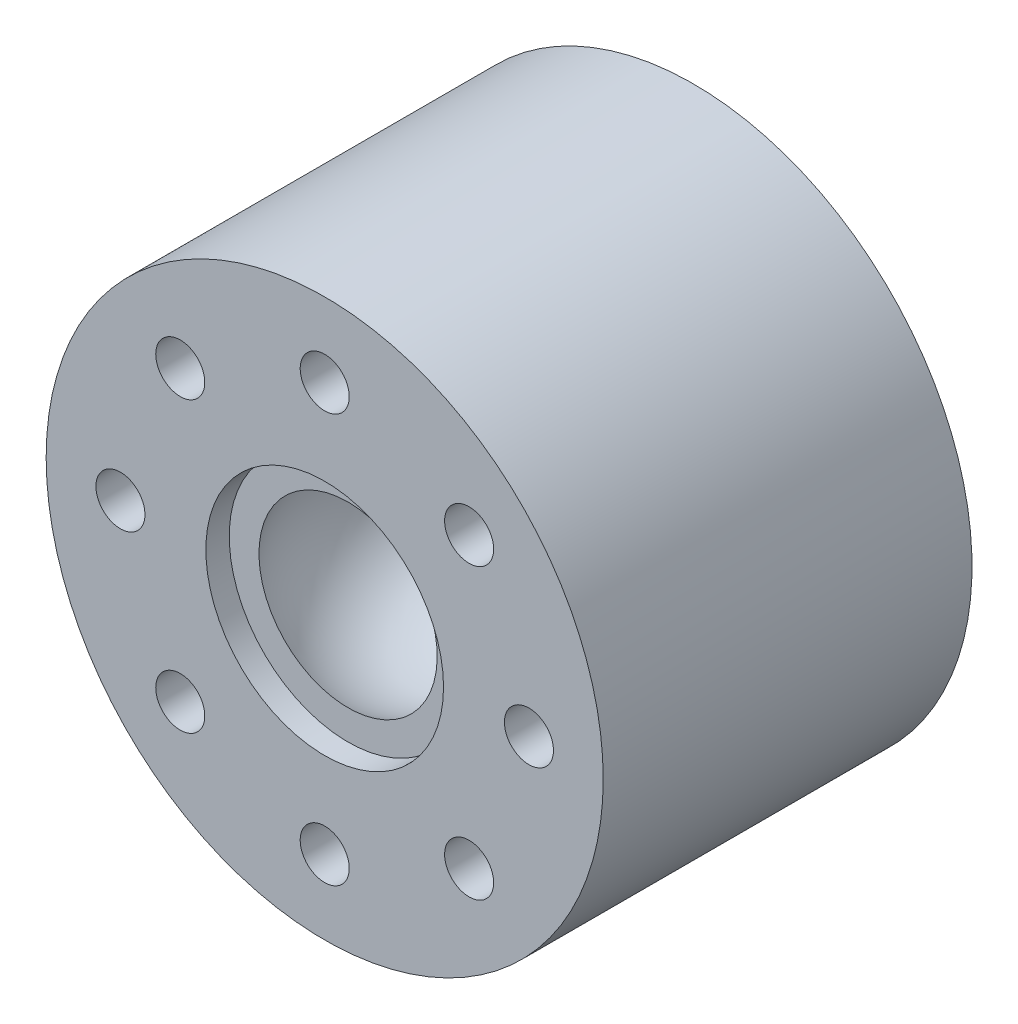
SolidWorks part; units mm, degrees
ref_plane "Front Plane" through (0, 0, 0) normal (0, 0, 1) x (1, 0, 0)
ref_plane "Top Plane" through (0, 0, 0) normal (0, 1, 0) x (1, 0, 0)
ref_plane "Right Plane" through (0, 0, 0) normal (1, 0, 0) x (0, 0, -1)
sketch "Sketch1" plane through (0, 0, 0) normal (0, 0, 1) x (1, 0, 0)
  circle A0 centre (0, 0) radius 37.5
  dimension "D1" = 75
extrude "Boss-Extrude1" add sketch "Sketch1" along normal blind 55
sketch "Sketch2" plane through (0, 0, 55) normal (0, 0, 1) x (1, 0, 0)
  circle A0 centre (0, 0) radius 16
  dimension "D1" = 32
extrude "Cut-Extrude1" cut sketch "Sketch2" against normal blind 16
sketch "Sketch3" plane through (0, 0, 39) normal (0, 0, 1) x (1, 0, 0)
  circle A0 centre (0, 0) radius 16
  dimension "D1" = 32
extrude "Cut-Extrude2" cut sketch "Sketch3" against normal blind 2.5
sketch "Sketch4" plane through (0, 0, 0) normal (1, 0, 0) x (0, 0, -1)
  line L0 (-12.7, 8.9281) -> (-12.7, 0)
  line L1 (-12.7, 0) -> (-36.5, 0)
  line L2 (-36.5, 0) -> (-36.5, 12)
  line L3 (0, -37.5) -> (0, 37.5) construction
  line L4 (-36.5, 16) -> (-36.5, -16) construction
  spline S0 degree 3 poles (-36.5, 12) (-28.3437, 16.5234) (-19.1659, 14.2615) (-12.7, 8.9281) knots 0 0 0 0 1 1 1 1
  dimension "D1" = 8.9281
  dimension "D2" = 12
  dimension "D3" = 12.7
revolve "Cut-Revolve1" cut sketch "Sketch4" angle 360 about L1
sketch "Sketch6" plane through (0, 0, 0) normal (0, 0, -1) x (-1, 0, 0)
  circle A0 centre (0, 0) radius 8.9297
  dimension "D1" = 17.8594
extrude "Cut-Extrude3" cut sketch "Sketch6" against normal blind 12.7
sketch "Sketch7" plane through (0, 0, 55) normal (0, 0, 1) x (1, 0, 0)
  circle A1 centre (0, 0) radius 37.5
  dimension "D1" = 75
extrude "Cut-Extrude4" cut sketch "Sketch7" against normal blind 15.35
sketch "Sketch9" plane through (0, 0, 0) normal (0, 0, -1) x (-1, 0, 0)
  circle A0 centre (0, 0) radius 27.5
  circle A1 centre (0, -27.5) radius 3.302
  circle A2 centre (-19.4454, -19.4454) radius 3.302
  circle A3 centre (-27.5, 0) radius 3.302
  circle A4 centre (-19.4454, 19.4454) radius 3.302
  circle A5 centre (0, 27.5) radius 3.302
  circle A6 centre (19.4454, 19.4454) radius 3.302
  circle A7 centre (27.5, 0) radius 3.302
  circle A8 centre (19.4454, -19.4454) radius 3.302
  point P21 (0, 0)
  dimension "D1" = 55
  dimension "D2" = 6.604
  dimension "D3" = 8
extrude "Cut-Extrude6" cut sketch "Sketch9" against normal through all contours A0 A7 | A0 A7 | A0 A8 | A0 A8 | A0 A1 | A0 A1 | A0 A2 | A0 A2 | A0 A3 | A0 A3 | A0 A4 | A0 A4 | A0 A5 | A0 A5 | A0 A6 | A0 A6
sketch "Sketch10" plane through (0, 0, 0) normal (0, 0, -1) x (-1, 0, 0)
  circle A0 centre (0, 0) radius 8.9297 construction
  circle A1 centre (-27.5, 0) radius 3.302 construction
  circle A2 centre (-19.4454, -19.4454) radius 3.302 construction
  circle A3 centre (0, -27.5) radius 3.302 construction
  circle A4 centre (19.4454, -19.4454) radius 3.302 construction
  circle A5 centre (27.5, 0) radius 3.302 construction
  circle A6 centre (19.4454, 19.4454) radius 3.302 construction
  circle A7 centre (0, 27.5) radius 3.302 construction
  circle A8 centre (-19.4454, 19.4454) radius 3.302 construction
  circle A9 centre (0, 0) radius 37.5 construction
  circle A10 centre (0, 0) radius 8.9297
  circle A11 centre (-27.5, 0) radius 3.302
  circle A12 centre (-19.4454, -19.4454) radius 3.302
  circle A13 centre (0, -27.5) radius 3.302
  circle A14 centre (19.4454, -19.4454) radius 3.302
  circle A15 centre (27.5, 0) radius 3.302
  circle A16 centre (19.4454, 19.4454) radius 3.302
  circle A17 centre (0, 27.5) radius 3.302
  circle A18 centre (-19.4454, 19.4454) radius 3.302
  circle A19 centre (0, 0) radius 37.5
extrude "Boss-Extrude2" add sketch "Sketch10" along normal blind 10
